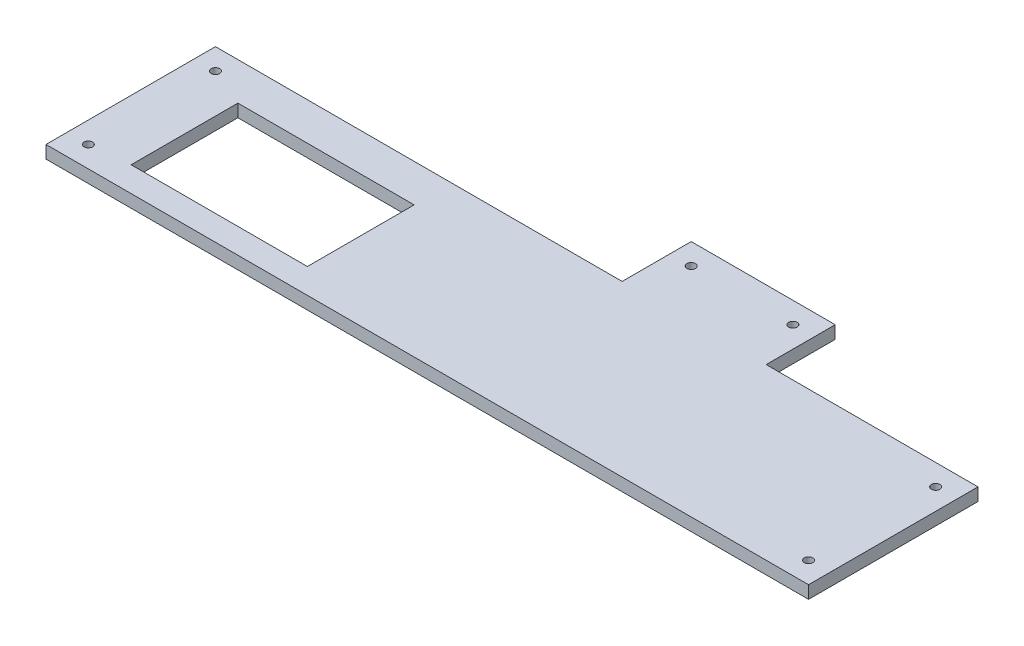
SolidWorks part; units mm, degrees
ref_plane "Front Plane" through (0, 0, 0) normal (0, 0, 1) x (1, 0, 0)
ref_plane "Top Plane" through (0, 0, 0) normal (0, 1, 0) x (1, 0, 0)
ref_plane "Right Plane" through (0, 0, 0) normal (1, 0, 0) x (0, 0, -1)
sketch "Sketch1" plane through (0, 0, 0) normal (0, 1, 0) x (1, 0, 0)
  line L0 (0, 0) -> (-450, 0) construction
  line L1 (0, 0) -> (0, 100) construction
  line L8 (450, 100) -> (-450, 100)
  line L9 (-450, 100) -> (-450, -100)
  line L10 (-450, -100) -> (450, -100)
  line L11 (450, -100) -> (450, 100)
  circle A4 centre (425, -75) radius 5
  circle A5 centre (425, 75) radius 5
  circle A6 centre (-425, -75) radius 5
  circle A7 centre (-425, 75) radius 5
  dimension "D4" = 25
  dimension "D1" = 900
  dimension "D2" = 200
  dimension "D3" = 25
extrude "Boss-Extrude1" add sketch "Sketch1" against normal blind 15
sketch "Sketch2" plane through (0, -15, 0) normal (0, -1, 0) x (1, 0, 0)
  line L1 (-379, 70.5) -> (-171, 70.5)
  line L2 (-379, 70.5) -> (-379, -55.5)
  line L3 (-379, -55.5) -> (-171, -55.5)
  line L4 (-171, 70.5) -> (-171, -55.5)
extrude "Shredder Opening" cut sketch "Sketch2" against normal through all
sketch "Sketch3" plane through (0, 0, 0) normal (0, 1, 0) x (1, 0, 0)
  line L0 (450, 100) -> (-450, 100) construction
  line L1 (200, 100) -> (30, 100)
  line L2 (200, 100) -> (200, 181.5)
  line L3 (200, 181.5) -> (30, 181.5)
  line L4 (30, 100) -> (30, 181.5)
  line L5 (180, -81.5) -> (180, 156.5) construction
  line L6 (50, 156.5) -> (180, 156.5) construction
  line L7 (50, -81.5) -> (50, 156.5) construction
  line L8 (115, 181.5) -> (115, 267.7218) construction
  circle A0 centre (175, 156.5) radius 5 construction
  circle A1 centre (175, 156.5) radius 5
  circle A2 centre (55, 156.5) radius 5
  dimension "D1" = 20
  dimension "D2" = 25
  dimension "D3" = 20
extrude "Legs add on" add sketch "Sketch3" against normal through all
